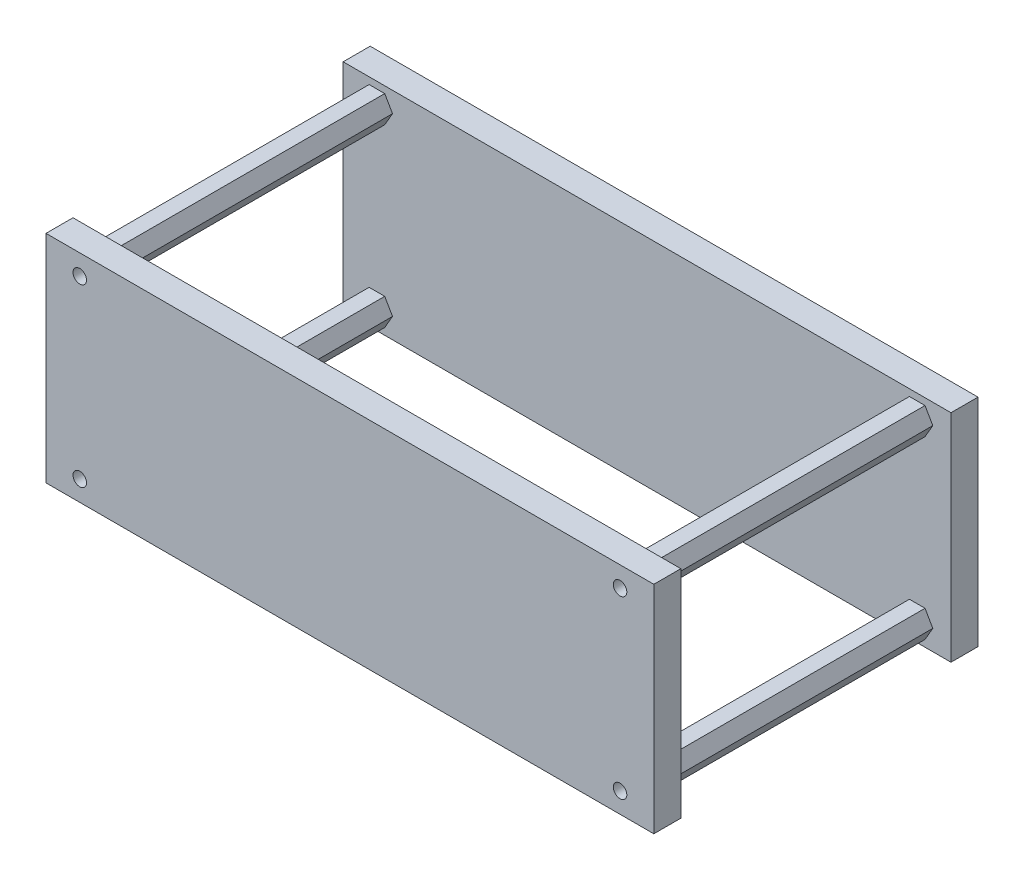
SolidWorks part; units mm, degrees
ref_plane "前视基准面" through (0, 0, 0) normal (0, 0, 1) x (1, 0, 0)
ref_plane "上视基准面" through (0, 0, 0) normal (0, 1, 0) x (1, 0, 0)
ref_plane "右视基准面" through (0, 0, 0) normal (1, 0, 0) x (0, 0, -1)
sketch "草图1" plane through (0, 0, 0) normal (0, 0, 1) x (1, 0, 0)
  line L1 (-22.5, 8) -> (22.5, 8)
  line L2 (-22.5, 8) -> (-22.5, -8)
  line L3 (-22.5, -8) -> (22.5, -8)
  line L4 (22.5, 8) -> (22.5, -8)
  line L5 (-22.5, 8) -> (22.5, -8) construction
  line L6 (-22.5, -8) -> (22.5, 8) construction
  circle A0 centre (-20, -6.5) radius 0.5
  circle A1 centre (-20, 6.5) radius 0.5
  circle A2 centre (20, 6.5) radius 0.5
  circle A3 centre (20, -6.5) radius 0.5
  point P0 (0, 0)
  dimension "D3" = 40
  dimension "D7" = 1
  dimension "D1" = 16
  dimension "D2" = 45
  dimension "D4" = 13
  dimension "D5" = 6.5
  dimension "D6" = 20
extrude "凸台-拉伸1" add sketch "草图1" along normal blind 2
sketch "草图2" plane through (0, 0, 2) normal (0, 0, 1) x (1, 0, 0)
  line L0 (0, 0) -> (0, 2.7019) construction
  line L1 (-18.8453, 6.5) -> (-19.4226, 7.5)
  line L2 (-19.4226, 7.5) -> (-20.5774, 7.5)
  line L3 (-20.5774, 7.5) -> (-21.1547, 6.5)
  line L4 (-21.1547, 6.5) -> (-20.5774, 5.5)
  line L5 (-20.5774, 5.5) -> (-19.4226, 5.5)
  line L6 (-19.4226, 5.5) -> (-18.8453, 6.5)
  line L7 (0, 0) -> (3.4919, 0) construction
  line L8 (19.4226, 5.5) -> (18.8453, 6.5)
  line L9 (20.5774, 5.5) -> (19.4226, 5.5)
  line L10 (21.1547, 6.5) -> (20.5774, 5.5)
  line L11 (20.5774, 7.5) -> (21.1547, 6.5)
  line L12 (19.4226, 7.5) -> (20.5774, 7.5)
  line L13 (18.8453, 6.5) -> (19.4226, 7.5)
  line L14 (18.8453, -6.5) -> (19.4226, -7.5)
  line L15 (19.4226, -7.5) -> (20.5774, -7.5)
  line L16 (20.5774, -7.5) -> (21.1547, -6.5)
  line L17 (21.1547, -6.5) -> (20.5774, -5.5)
  line L18 (20.5774, -5.5) -> (19.4226, -5.5)
  line L19 (19.4226, -5.5) -> (18.8453, -6.5)
  line L20 (-19.4226, -5.5) -> (-18.8453, -6.5)
  line L21 (-20.5774, -5.5) -> (-19.4226, -5.5)
  line L22 (-21.1547, -6.5) -> (-20.5774, -5.5)
  line L23 (-20.5774, -7.5) -> (-21.1547, -6.5)
  line L24 (-19.4226, -7.5) -> (-20.5774, -7.5)
  line L25 (-18.8453, -6.5) -> (-19.4226, -7.5)
  circle A0 centre (-20, 6.5) radius 1 construction
  circle A1 centre (20, 6.5) radius 1 construction
  circle A2 centre (20, -6.5) radius 1 construction
  circle A3 centre (-20, -6.5) radius 1 construction
  dimension "D1" = 2
extrude "凸台-拉伸2" add sketch "草图2" along normal blind 20
sketch "草图3" plane through (0, 0, 22) normal (0, 0, 1) x (1, 0, 0)
  line L4 (22.5, -8) -> (22.5, 8)
  line L5 (22.5, 8) -> (-22.5, 8)
  line L6 (-22.5, 8) -> (-22.5, -8)
  line L7 (-22.5, -8) -> (22.5, -8)
  line L8 (22.5, -8) -> (22.5, 8)
  line L9 (22.5, 8) -> (-22.5, 8)
  line L10 (-22.5, 8) -> (-22.5, -8)
  line L11 (-22.5, -8) -> (22.5, -8)
  circle A1 centre (20, 6.5) radius 0.5
  circle A2 centre (20, 6.5) radius 0.5
  circle A3 centre (-20, -6.5) radius 0.5
  circle A4 centre (-20, -6.5) radius 0.5
  circle A5 centre (-20, 6.5) radius 0.5
  circle A6 centre (-20, 6.5) radius 0.5
  circle A7 centre (20, -6.5) radius 0.5
  circle A8 centre (20, -6.5) radius 0.5
  dimension "D1" = 0
  dimension "D2" = 0
  dimension "D3" = 0
  dimension "D4" = 0
  dimension "D5" = 0
extrude "凸台-拉伸3" add sketch "草图3" along normal blind 2
